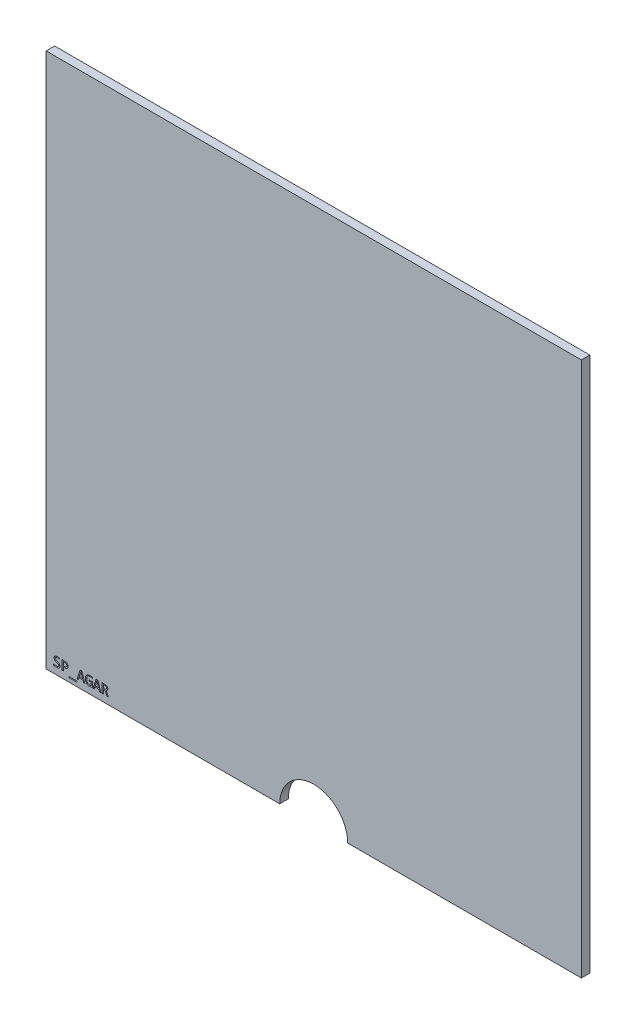
SolidWorks part; units mm, degrees
material "PVC Rigid"
ref_plane "Front Plane" through (0, 0, 0) normal (0, 0, 1) x (1, 0, 0)
ref_plane "Top Plane" through (0, 0, 0) normal (0, 1, 0) x (1, 0, 0)
ref_plane "Right Plane" through (0, 0, 0) normal (1, 0, 0) x (0, 0, -1)
sketch "Sketch1" plane through (0, 0, 0) normal (0, 0, 1) x (1, 0, 0)
  line L1 (0, 0) -> (199.873, 0)
  line L2 (0, 0) -> (0, 199.873)
  line L3 (0, 199.873) -> (199.873, 199.873)
  line L4 (199.873, 0) -> (199.873, 199.873)
  dimension "D1" = 199.873
extrude "Boss-Extrude1" add sketch "Sketch1" along normal blind 3.175
sketch "Sketch3" plane through (0, 0, 3.175) normal (0, 0, 1) x (1, 0, 0)
  line L0 (99.9365, 199.873) -> (99.9365, 0) construction
  line L1 (199.873, 199.873) -> (0, 199.873) construction
  line L2 (0, 0) -> (199.873, 0) construction
  line L3 (87.2365, 0) -> (112.6365, 0)
  arc A0 (112.6365, 0) -> (87.2365, 0) centre (99.9365, 0) ccw
  dimension "D1" = 25.4
extrude "Cut-Extrude3" cut sketch "Sketch3" against normal blind 3.175
sketch "Sketch4" plane through (0, 0, 3.175) normal (0, 0, 1) x (1, 0, 0)
  line L0 (2.54, 2.54) -> (199.873, 2.54) construction
  line L1 (199.873, 0) -> (199.873, 199.873) construction
  line L3 (0, 0) -> (2.54, 0) construction
  line L4 (0, 0) -> (0, 2.54) construction
  line L5 (0, 2.54) -> (2.54, 2.54) construction
  line L6 (2.54, 0) -> (2.54, 2.54) construction
  text T0 "SP_AGAR" font "Consolas" height 3.5
  dimension "D1" = 2.54
extrude "Cut-Extrude4" cut sketch "Sketch4" against normal blind 1.5875
